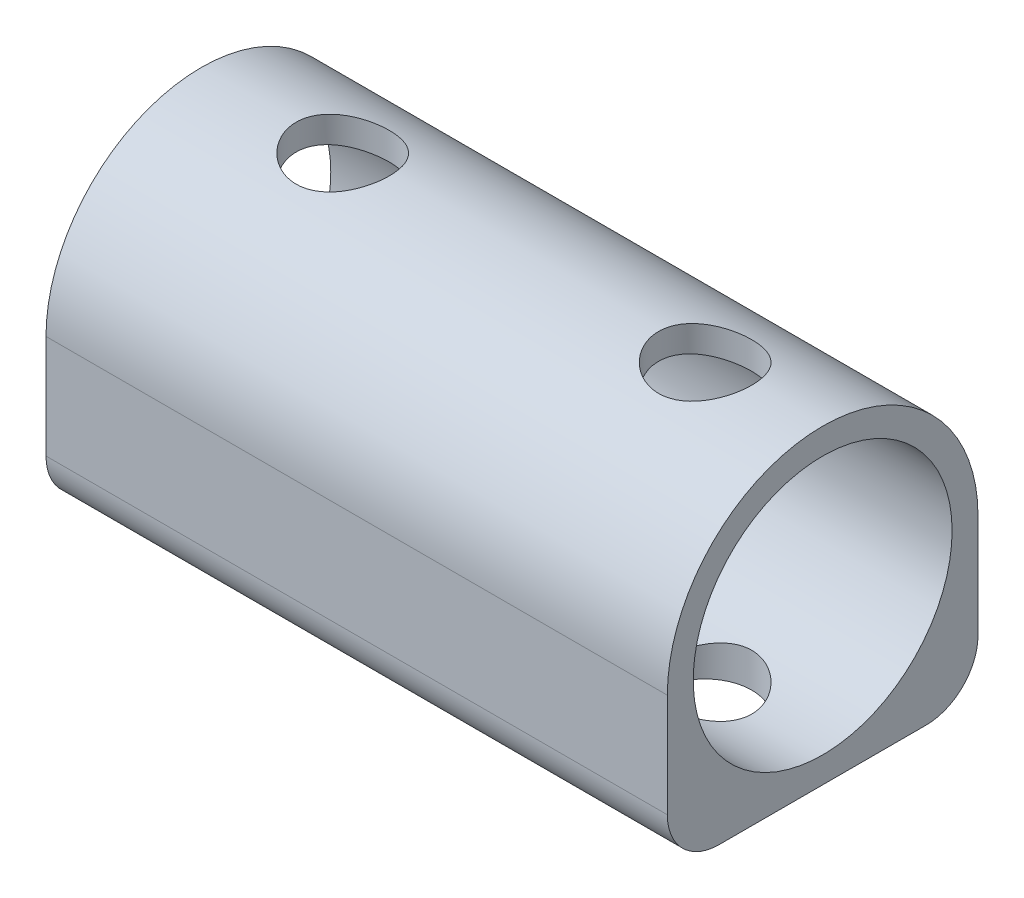
SolidWorks part; units mm, degrees
ref_plane "Front" through (0, 0, 0) normal (0, 0, 1) x (1, 0, 0)
ref_plane "Top" through (0, 0, 0) normal (0, 1, 0) x (1, 0, 0)
ref_plane "Right" through (0, 0, 0) normal (1, 0, 0) x (0, 0, -1)
sketch "Sketch1" plane through (0, 0, 0) normal (1, 0, 0) x (0, 0, -1)
  line L0 (19.05, 0) -> (19.05, -19.05)
  line L1 (-19.05, 0) -> (-19.05, -19.05)
  line L2 (-19.05, -19.05) -> (19.05, -19.05)
  arc A1 (19.05, 0) -> (-19.05, 0) centre (0, 0) ccw
  dimension "D4" = 19.05
  dimension "D5" = 38.1
extrude "Base-Extrude" add sketch "Sketch1" against normal blind 76.2
sketch "Sketch3" plane through (0, 0, 0) normal (1, 0, 0) x (0, 0, -1)
  circle A0 centre (0, 0) radius 15.875
  dimension "D1" = 31.75
extrude "Cut-Extrude2" cut sketch "Sketch3" against normal through all
sketch "Sketch2" plane through (0, -19.05, 0) normal (0, -1, 0) x (1, 0, 0)
  line L0 (-36.6348, 0) -> (-36.6348, -46.1898) construction
  line L3 (50, 0) -> (-50, 0) construction
  circle A0 centre (-14.4098, 0) radius 5.715
  circle A1 centre (-58.8598, 0) radius 5.715
  dimension "D1" = 44.45
  dimension "D2" = 11.43
extrude "Cut-Extrude1" cut sketch "Sketch2" against normal through all
fillet "Fillet1" radius 6.35 2 edges at (-38.1, -19.05, 19.05) (-38.1, -19.05, -19.05)
